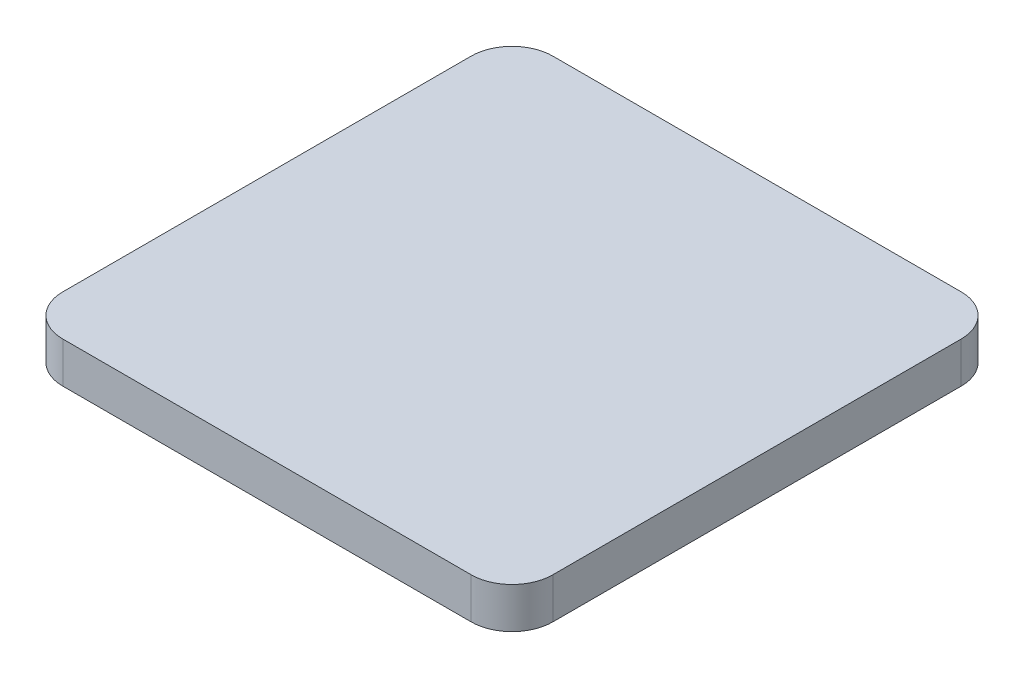
SolidWorks part; units mm, degrees
ref_plane "Front Plane" through (0, 0, 0) normal (0, 0, 1) x (1, 0, 0)
ref_plane "Top Plane" through (0, 0, 0) normal (0, 1, 0) x (1, 0, 0)
ref_plane "Right Plane" through (0, 0, 0) normal (1, 0, 0) x (0, 0, -1)
sketch "Sketch2" plane through (0, 0, 0) normal (0, 1, 0) x (1, 0, 0)
  line L1 (-30, 30) -> (30, 30)
  line L2 (-30, 30) -> (-30, -30)
  line L3 (-30, -30) -> (30, -30)
  line L4 (30, 30) -> (30, -30)
  line L5 (-30, 30) -> (30, -30) construction
  line L6 (-30, -30) -> (30, 30) construction
  point P0 (0, 0)
  dimension "D1" = 60
  dimension "D2" = 60
extrude "Boss-Extrude1" add sketch "Sketch2" along normal blind 5
fillet "Fillet1" radius 5 4 edges at (30, 2.5, 30) (30, 2.5, -30) (-30, 2.5, -30) (-30, 2.5, 30)
